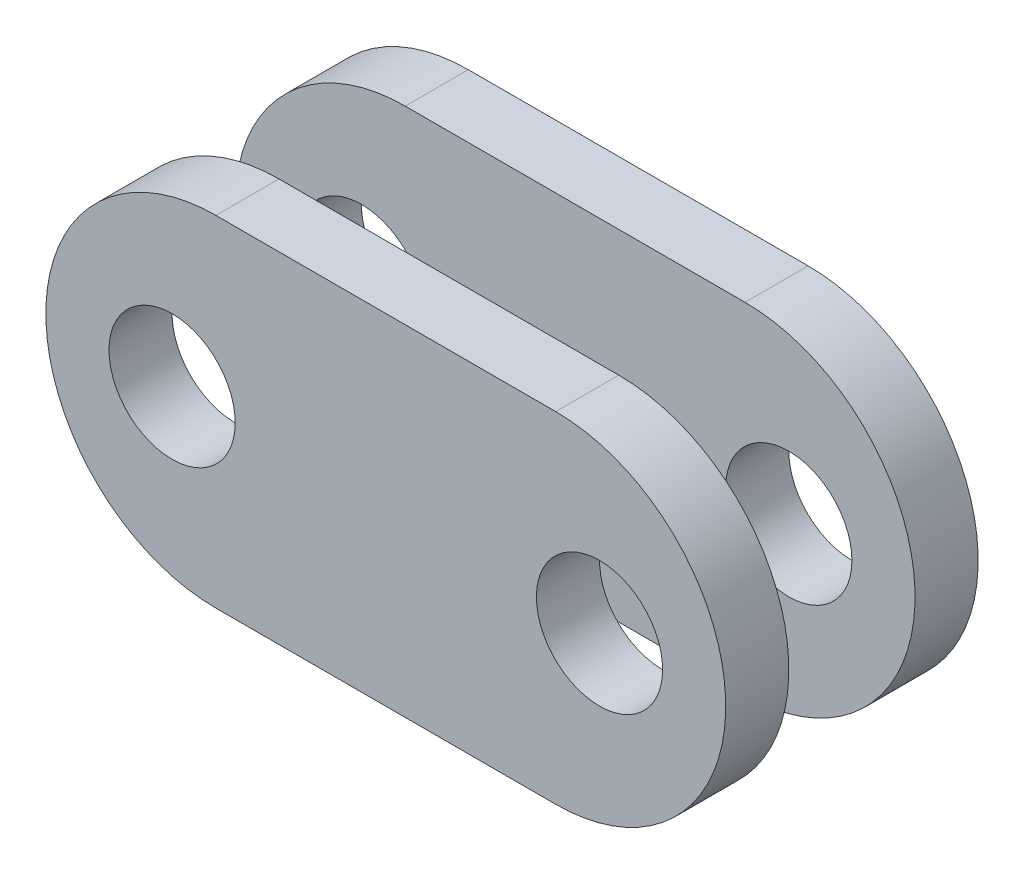
SolidWorks part; units mm, degrees
ref_plane "Front Plane" through (0, 0, 0) normal (0, 0, 1) x (1, 0, 0)
ref_plane "Top Plane" through (0, 0, 0) normal (0, 1, 0) x (1, 0, 0)
ref_plane "Right Plane" through (0, 0, 0) normal (1, 0, 0) x (0, 0, -1)
sketch "Sketch1" plane through (0, 0, 0) normal (0, 0, 1) x (1, 0, 0)
  line L0 (-3.4192, 0) -> (3.4192, 0) construction
  line L1 (-3.4192, 3.4228) -> (3.4192, 3.4228)
  line L2 (-3.4192, -3.4228) -> (3.4192, -3.4228)
  line L3 (0, -0.9116) -> (0, 0.9272) construction
  arc A0 (-3.4192, 3.4228) -> (-3.4192, -3.4228) centre (-3.4192, 0) ccw
  arc A1 (3.4192, -3.4228) -> (3.4192, 3.4228) centre (3.4192, 0) ccw
  point P3 (0, 0)
  dimension "D1" = 3.4192
  dimension "D2" = 3.4192
extrude "Boss-Extrude1" add sketch "Sketch1" along normal blind 7.62
sketch "Sketch2" plane through (0, 3.4228, 0) normal (0, 1, 0) x (1, 0, 0)
  line L0 (-6.842, 0) -> (-6.842, -7.62) construction
  line L1 (-6.842, -6.35) -> (6.842, -6.35)
  line L2 (-6.842, -6.35) -> (-6.842, -1.27)
  line L3 (-6.842, -1.27) -> (6.842, -1.27)
  line L4 (6.842, -6.35) -> (6.842, -1.27)
  line L5 (6.842, -7.62) -> (6.842, 0) construction
  line L6 (-3.4192, 0) -> (-6.842, 0) construction
  line L7 (-6.842, -7.62) -> (-3.4192, -7.62) construction
  dimension "D1" = 1.27
  dimension "D2" = 1.27
sketch "Sketch3" plane through (0, 0, 7.62) normal (0, 0, 1) x (1, 0, 0)
  circle A0 centre (-4.3013, 0) radius 1.27
sketch "Sketch5" plane through (0, 3.4228, 0) normal (0, 1, 0) x (1, 0, 0)
  line L0 (6.842, -7.62) -> (6.842, 0) construction
  line L1 (-6.842, -7.62) -> (6.842, -7.62)
  line L2 (-6.842, -7.62) -> (-6.842, -6.35)
  line L3 (-6.842, -6.35) -> (6.842, -6.35)
  line L4 (6.842, -7.62) -> (6.842, -6.35)
  dimension "D1" = 1.27
extrude "Cut-Extrude5" cut sketch "Sketch5" against normal through all
extrude "Cut-Extrude6" cut sketch "Sketch3" against normal through all contours A0
mirror "Mirror2" about plane through (0, 0, 0) normal (1, 0, 0) of "Cut-Extrude6"
extrude "Cut-Extrude7" [suppressed] cut sketch "Sketch2" against normal through all
sketch "Sketch6" plane through (0, 3.4228, 0) normal (0, 1, 0) x (1, 0, 0)
  line L0 (6.842, -6.35) -> (6.842, 0) construction
  line L1 (-6.842, 0) -> (6.842, 0)
  line L2 (-6.842, 0) -> (-6.842, -1.27)
  line L3 (-6.842, -1.27) -> (6.842, -1.27)
  line L4 (6.842, 0) -> (6.842, -1.27)
  dimension "D1" = 1.27
extrude "Cut-Extrude8" cut sketch "Sketch6" against normal through all
sketch "Sketch7" plane through (0, 3.4228, 0) normal (0, 1, 0) x (1, 0, 0)
  line L0 (-6.842, -1.27) -> (-6.842, -6.35) construction
  line L1 (-6.842, -2.54) -> (6.842, -2.54)
  line L2 (-6.842, -2.54) -> (-6.842, -5.08)
  line L3 (-6.842, -5.08) -> (6.842, -5.08)
  line L4 (6.842, -2.54) -> (6.842, -5.08)
  line L5 (6.842, -6.35) -> (6.842, -1.27) construction
  line L6 (-3.4192, -1.27) -> (-6.842, -1.27) construction
  line L7 (-6.842, -6.35) -> (-3.4192, -6.35) construction
  dimension "D1" = 1.27
  dimension "D2" = 1.27
extrude "Cut-Extrude9" cut sketch "Sketch7" against normal through all
equation "\"D1@Sketch1\"= \"D2@Sketch1\""
